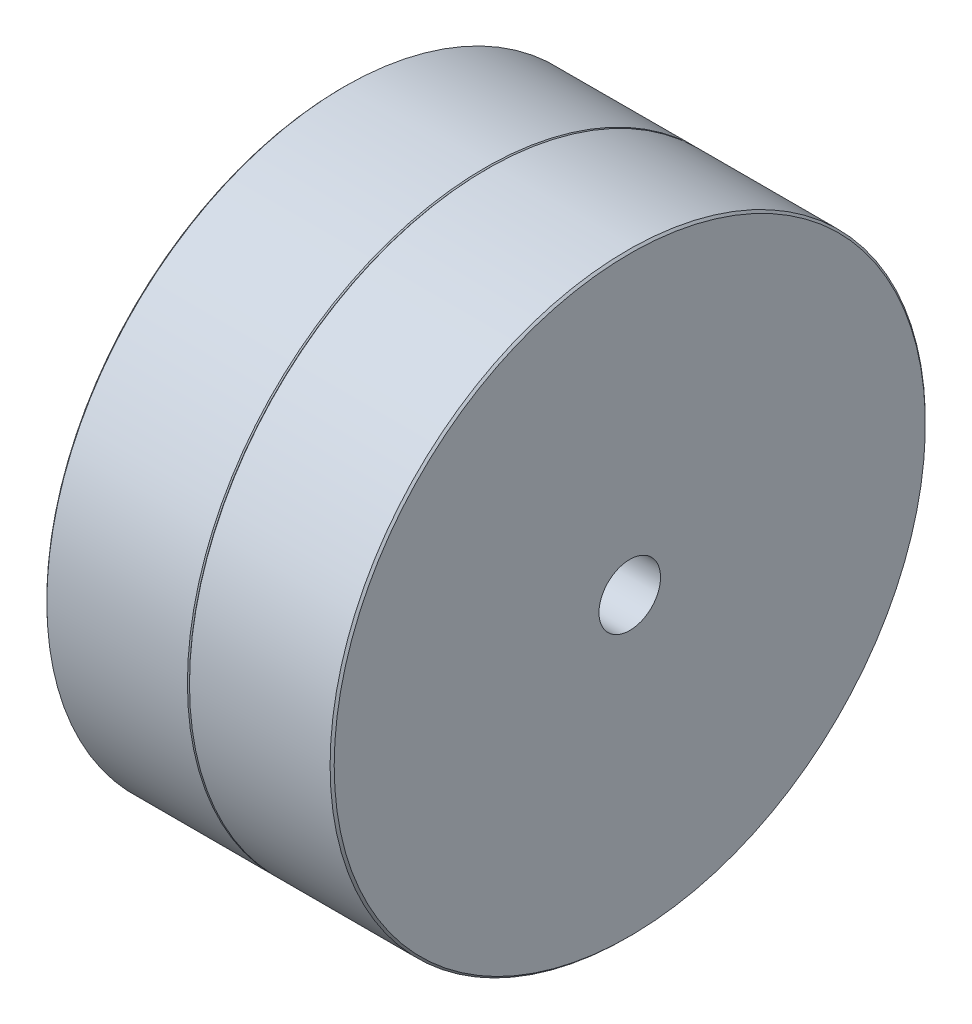
SolidWorks part; units mm, degrees
material "橡胶"
ref_plane "前视基准面" through (0, 0, 0) normal (0, 0, 1) x (1, 0, 0)
ref_plane "上视基准面" through (0, 0, 0) normal (0, 1, 0) x (1, 0, 0)
ref_plane "右视基准面" through (0, 0, 0) normal (1, 0, 0) x (0, 0, -1)
sketch "草图1" plane through (0, 0, 0) normal (0, 0, 1) x (1, 0, 0)
  line L0 (0, 0) -> (73.4774, 0) construction
  line L1 (0, 3) -> (0, 29)
  line L2 (0, 29) -> (13.9, 29)
  line L3 (28, 29) -> (28, 13)
  line L4 (28, 13) -> (28, 10)
  line L5 (28, 10) -> (28, 3)
  line L6 (0, 3) -> (28, 3)
  line L7 (14, 32.5) -> (14, 3) construction
  line L8 (13.9, 29) -> (14, 28.9)
  line L9 (14, 28.9) -> (14.1, 29)
  line L10 (14.1, 29) -> (28, 29)
  dimension "D1" = 6
  dimension "D2" = 28
  dimension "D3" = 28
  dimension "D4" = 3
  dimension "D5" = 180
  dimension "D6" = 20
  dimension "D7" = 58
  dimension "D8" = 0.2
revolve "旋转1" add sketch "草图1" angle 360 about L0
chamfer "倒角1" distance 0.2 angle 45 3 edges at (0, 0, 3) (28, 0, 29) (0, 0, 29)
